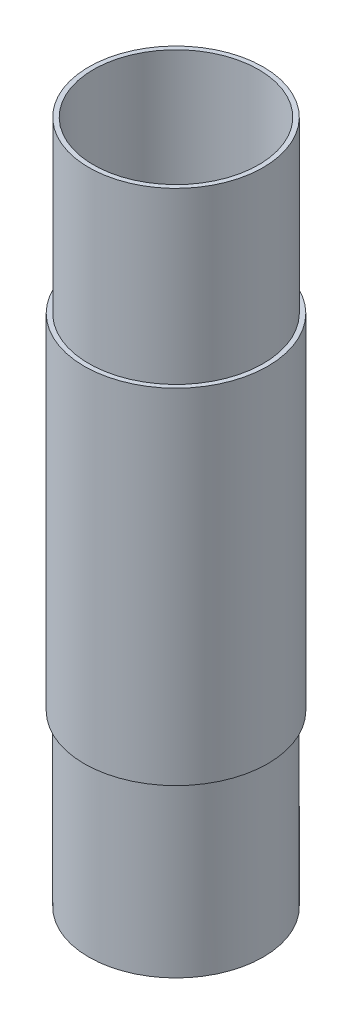
SolidWorks part; units mm, degrees
ref_plane "Front Plane" through (0, 0, 0) normal (0, 0, 1) x (1, 0, 0)
ref_plane "Top Plane" through (0, 0, 0) normal (0, 1, 0) x (1, 0, 0)
ref_plane "Right Plane" through (0, 0, 0) normal (1, 0, 0) x (0, 0, -1)
sketch "Sketch1" plane through (0, 0, 0) normal (0, 1, 0) x (1, 0, 0)
  circle A0 centre (0, 0) radius 40
  dimension "D1" = 80
extrude "Extrude-Thin1" add sketch "Sketch1" along normal blind 150 thin thin type one direction reverse wall 3
sketch "Sketch2" plane through (0, 0, 0) normal (0, -1, 0) x (1, 0, 0)
  circle A3 centre (0, 0) radius 37 construction
  circle A4 centre (0, 0) radius 37
extrude "Extrude-Thin2" add sketch "Sketch2" along normal blind 74 separate body thin thin type mid plane wall 2
sketch "Sketch4" plane through (0, 0, 0) normal (0, 1, 0) x (1, 0, 0)
  circle A1 centre (0, 0) radius 38
  circle A2 centre (0, 0) radius 38
  circle A3 centre (0, 0) radius 36 construction
  circle A4 centre (0, 0) radius 36
  dimension "D1" = 0
sketch "Sketch7" plane through (0, 150, 0) normal (0, 1, 0) x (1, 0, 0)
  circle A0 centre (0, 0) radius 38 construction
  circle A1 centre (0, 0) radius 38
extrude "Extrude-Thin7" add sketch "Sketch7" along normal blind 74 separate body thin thin type one direction reverse wall 1
extrude "Boss-Extrude2" add sketch "Sketch4" along normal through all
equation "\"grosor fuselaje\"=3"
equation "\"D5@Extrude-Thin1\"=\"grosor fuselaje\""
equation "\"largo brazo\"=74"
equation "\"D1@Extrude-Thin2\"=\"largo brazo\""
equation "\"Diametro fuselaje\"=80"
equation "\"D1@Sketch1\"=\"Diametro fuselaje\""
equation "\"largo cople\"= 150"
equation "\"D1@Extrude-Thin1\"=\"largo cople\""
equation "\"largo del brazo\"=74"
equation "\"D1@Extrude-Thin7\"=\"largo del brazo\""
equation "\"grosor del brazo\"=1"
equation "\"D5@Extrude-Thin7\"=\"grosor del brazo\""
